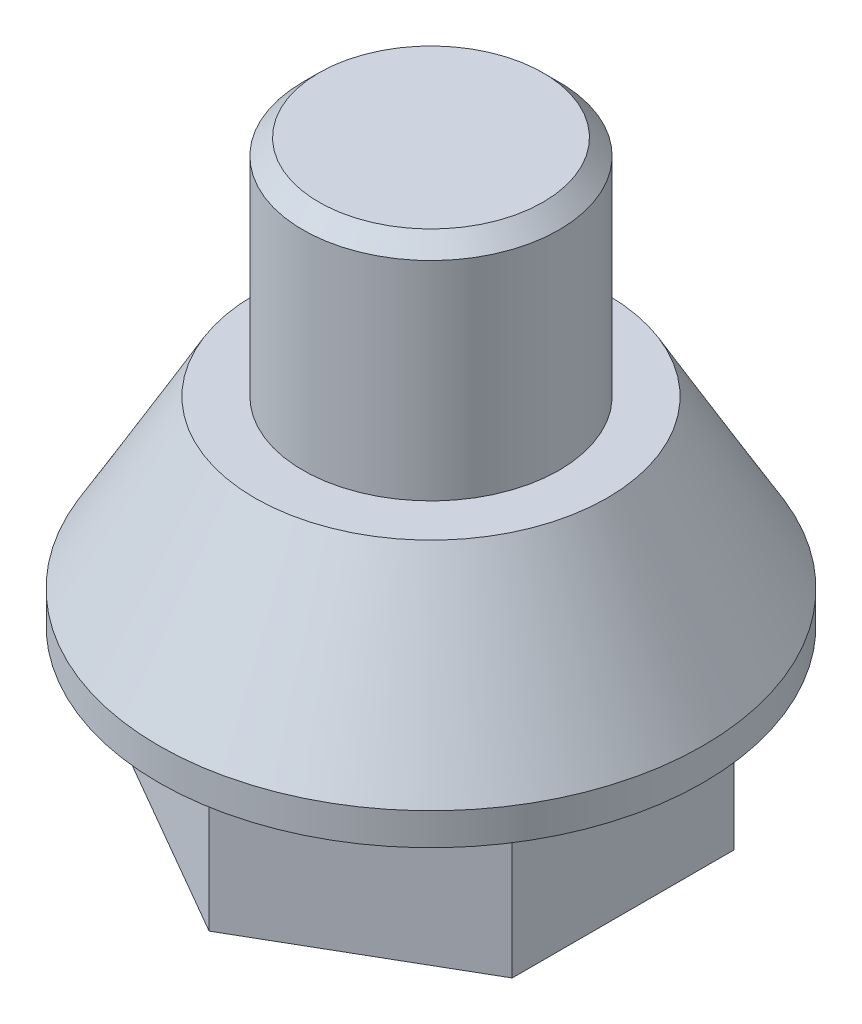
SolidWorks part; units mm, degrees
ref_plane "Front Plane" through (0, 0, 0) normal (0, 0, 1) x (1, 0, 0)
ref_plane "Top Plane" through (0, 0, 0) normal (0, 1, 0) x (1, 0, 0)
ref_plane "Right Plane" through (0, 0, 0) normal (1, 0, 0) x (0, 0, -1)
sketch "Sketch1" plane through (0, 0, 0) normal (0, 1, 0) x (1, 0, 0)
  line L0 (0, 6.9282) -> (0, -6.9282) construction
  line L1 (-6, -3.4641) -> (6, 3.4641) construction
  line L2 (6, -3.4641) -> (-6, 3.4641) construction
  line L3 (0, 6.9282) -> (6, 3.4641)
  line L4 (6, 3.4641) -> (6, -3.4641)
  line L5 (6, -3.4641) -> (0, -6.9282)
  line L6 (0, -6.9282) -> (-6, -3.4641)
  line L7 (-6, -3.4641) -> (-6, 3.4641)
  line L8 (-6, 3.4641) -> (0, 6.9282)
  point P6 (-24.2392, 13.9945)
  dimension "D1" = 60
  dimension "D2" = 60
  dimension "D3" = 12
extrude "Boss-Extrude1" add sketch "Sketch1" along normal blind 4.8
sketch "Sketch2" plane through (0, 4.8, 0) normal (0, 1, 0) x (1, 0, 0)
  circle A0 centre (0, 0) radius 8.5
  dimension "D1" = 17
extrude "Boss-Extrude2" add sketch "Sketch2" along normal blind 1
sketch "Sketch3" plane through (0, 0, 0) normal (0, 0, 1) x (1, 0, 0)
  line L0 (0, 5.8) -> (8.5, 5.8)
  line L1 (8.5, 5.8) -> (5.5, 10.9962)
  line L2 (5.5, 10.9962) -> (4, 10.9962)
  line L3 (4, 10.9962) -> (4, 17.9962)
  line L4 (4, 17.9962) -> (0, 17.9962)
  line L5 (0, 5.8) -> (0, 17.9962)
  line L6 (8.5, 5.8) -> (-8.5, 5.8) construction
  point P9 (0, 0)
  point P11 (4, 13.5363)
  dimension "D1" = 4
  dimension "D2" = 1.5
  dimension "D3" = 7
  dimension "D4" = 60
revolve "Revolve1" add sketch "Sketch3" angle 360 about L5
chamfer "Chamfer1" distance 0.5 angle 45 1 edges at (4, 17.9962, 0)
